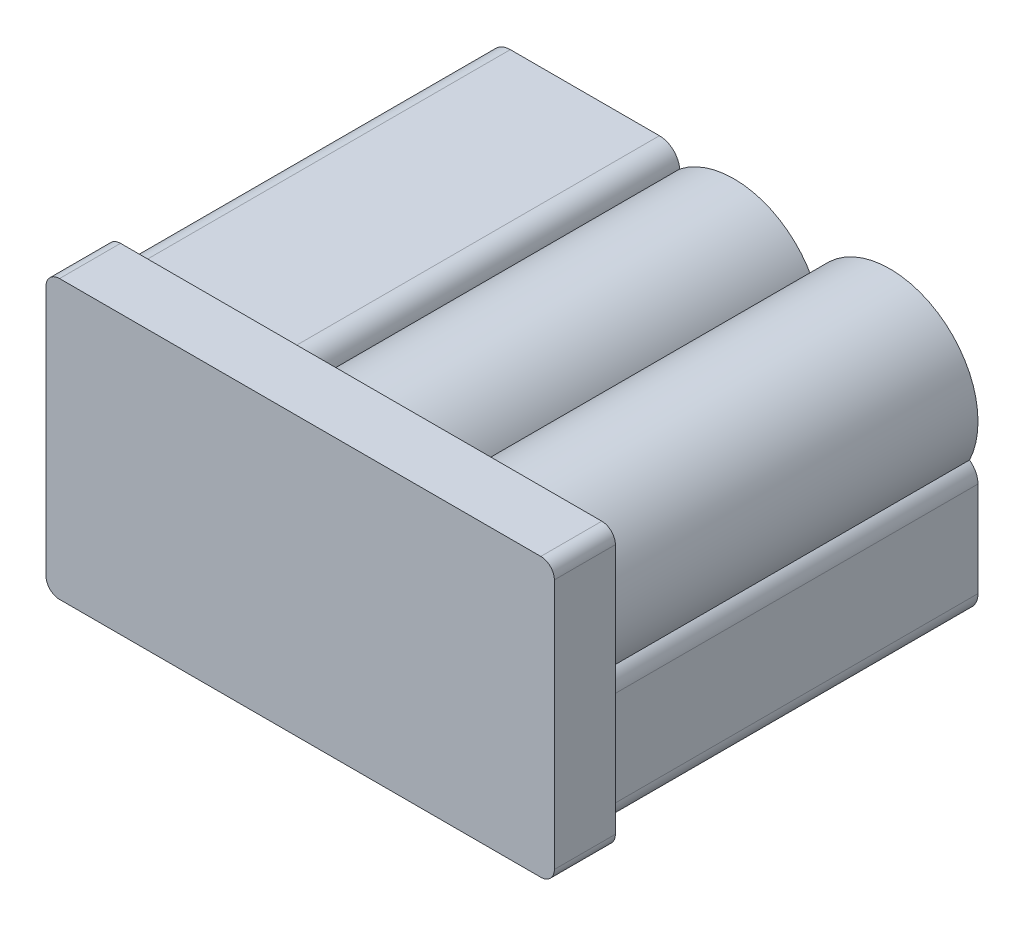
SolidWorks part; units mm, degrees
ref_plane "Front Plane" through (0, 0, 0) normal (0, 0, 1) x (1, 0, 0)
ref_plane "Top Plane" through (0, 0, 0) normal (0, 1, 0) x (1, 0, 0)
ref_plane "Right Plane" through (0, 0, 0) normal (1, 0, 0) x (0, 0, -1)
sketch "Sketch1" plane through (0, 0, 0) normal (0, 0, 1) x (1, 0, 0)
  line L1 (-119.0625, -65.0875) -> (119.0625, -65.0875)
  line L2 (-119.0625, -65.0875) -> (-119.0625, 65.0875)
  line L3 (-119.0625, 65.0875) -> (119.0625, 65.0875)
  line L4 (119.0625, -65.0875) -> (119.0625, 65.0875)
  line L5 (-119.0625, -65.0875) -> (119.0625, 65.0875) construction
  line L6 (-119.0625, 65.0875) -> (119.0625, -65.0875) construction
  point P0 (0, 0)
  dimension "D1" = 238.125
  dimension "D2" = 130.175
extrude "Boss-Extrude1" add sketch "Sketch1" along normal blind 203.2
sketch "Sketch2" plane through (0, 0, 0) normal (0, 0, -1) x (-1, 0, 0)
  line L0 (-73.025, 19.05) -> (0, 19.05) construction
  line L2 (0, 19.05) -> (73.025, 19.05) construction
  line L3 (73.025, 19.05) -> (73.025, -19.05) construction
  line L4 (73.025, -19.05) -> (0, -19.05) construction
  line L6 (0, -19.05) -> (-73.025, -19.05) construction
  line L7 (-73.025, -19.05) -> (-73.025, 19.05) construction
  line L8 (-119.0625, -65.0875) -> (-119.0625, 65.0875) construction
  line L9 (-73.025, 19.05) -> (73.025, -19.05) construction
  line L10 (119.0625, 65.0875) -> (-119.0625, -65.0875) construction
  line L11 (34.925, -3.175) -> (104.775, -3.175)
  line L13 (114.3, -60.325) -> (-114.3, -60.325) construction
  line L14 (114.3, -60.325) -> (114.3, 60.325) construction
  line L15 (114.3, 60.325) -> (-114.3, 60.325) construction
  line L16 (-114.3, -60.325) -> (-114.3, 60.325) construction
  line L17 (114.3, -60.325) -> (-114.3, 60.325) construction
  line L18 (114.3, 60.325) -> (-114.3, -60.325) construction
  line L19 (25.4, 6.35) -> (25.4, 50.8)
  line L20 (114.3, 6.35) -> (114.3, 50.8)
  line L21 (34.925, 60.325) -> (104.775, 60.325)
  line L22 (25.4, -3.175) -> (114.3, 60.325) construction
  line L23 (114.3, -3.175) -> (25.4, 60.325) construction
  line L24 (-34.925, -60.325) -> (-104.775, -60.325)
  line L25 (-25.4, -50.8) -> (-25.4, -6.35)
  line L26 (-114.3, -50.8) -> (-114.3, -6.35)
  line L27 (-34.925, 3.175) -> (-104.775, 3.175)
  line L28 (-25.4, -60.325) -> (-114.3, 3.175) construction
  line L29 (-114.3, -60.325) -> (-25.4, 3.175) construction
  circle A0 centre (-73.025, 19.05) radius 41.275
  circle A1 centre (0, 19.05) radius 41.275
  arc A3 (104.775, 60.325) -> (114.3, 50.8) centre (104.775, 50.8) cw
  arc A4 (104.775, -3.175) -> (114.3, 6.35) centre (104.775, 6.35) ccw
  circle A6 centre (0, -19.05) radius 41.275
  circle A7 centre (73.025, -19.05) radius 41.275
  arc A8 (25.4, 50.8) -> (34.925, 60.325) centre (34.925, 50.8) cw
  arc A9 (25.4, 6.35) -> (34.925, -3.175) centre (34.925, 6.35) ccw
  arc A10 (-25.4, -6.35) -> (-34.925, 3.175) centre (-34.925, -6.35) ccw
  arc A11 (-114.3, -6.35) -> (-104.775, 3.175) centre (-104.775, -6.35) cw
  arc A12 (-25.4, -50.8) -> (-34.925, -60.325) centre (-34.925, -50.8) cw
  arc A13 (-114.3, -50.8) -> (-104.775, -60.325) centre (-104.775, -50.8) ccw
  point P9 (69.85, 28.575)
  point P22 (0, 0)
  point P23 (0, 0)
  point P31 (-69.85, -28.575)
  dimension "D3" = 82.55
  dimension "D4" = 9.525
  dimension "D1" = 120.65
  dimension "D2" = 228.6
  dimension "D5" = 88.9
  dimension "D6" = 63.5
extrude "Cut-Extrude1" cut sketch "Sketch2" against normal blind 174.625
fillet "Fillet1" radius 6.35 4 edges at (-119.0625, -65.0875, 188.9125) (-119.0625, 65.0875, 188.9125) (119.0625, -65.0875, 188.9125) (119.0625, 65.0875, 188.9125)
